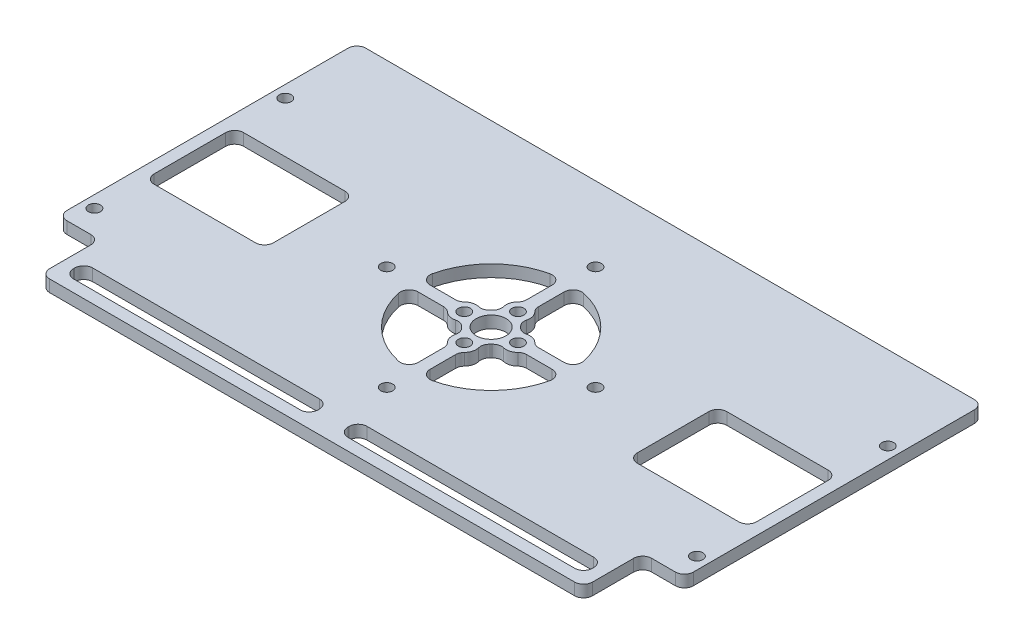
SolidWorks part; units mm, degrees
ref_plane "Front Plane" through (0, 0, 0) normal (0, 0, 1) x (1, 0, 0)
ref_plane "Top Plane" through (0, 0, 0) normal (0, 1, 0) x (1, 0, 0)
ref_plane "Right Plane" through (0, 0, 0) normal (1, 0, 0) x (0, 0, -1)
sketch "Sketch2" plane through (0, 0, 0) normal (0, 1, 0) x (1, 0, 0)
  line L0 (0, -30) -> (105, -30) construction
  line L1 (0, 0) -> (105, 0)
  line L2 (0, 0) -> (0, -60)
  line L3 (0, -60) -> (105, -60)
  line L4 (105, 0) -> (105, -60)
  line L5 (52.5, 0) -> (52.5, -60) construction
  line L6 (55, -54.8) -> (55, -58)
  line L7 (9, -54.8) -> (50, -54.8)
  line L8 (9, -54.8) -> (9, -58)
  line L9 (9, -58) -> (50, -58)
  line L10 (50, -54.8) -> (50, -58)
  line L11 (96, -54.8) -> (96, -58)
  line L12 (96, -58) -> (55, -58)
  line L13 (96, -54.8) -> (55, -54.8)
  line L14 (51.5, -17.0385) -> (51.5, -23.7679)
  line L15 (53.5, -17.0385) -> (53.5, -23.7679)
  line L16 (65.4615, -29) -> (58.7321, -29)
  line L17 (65.4615, -31) -> (58.7321, -31)
  line L18 (53.5, -42.9615) -> (53.5, -36.2321)
  line L19 (51.5, -42.9615) -> (51.5, -36.2321)
  line L20 (39.5385, -31) -> (46.2679, -31)
  line L21 (39.5385, -29) -> (46.2679, -29)
  line L22 (0, -50.1) -> (7, -50.1)
  line L23 (7, -50.1) -> (7, -60)
  line L24 (98, -50.1) -> (98, -60)
  line L25 (105, -50.1) -> (98, -50.1)
  line L26 (83, -22.5) -> (83, -37.5)
  line L27 (2, -22.5) -> (22, -22.5)
  line L28 (2, -22.5) -> (2, -37.5)
  line L29 (2, -37.5) -> (22, -37.5)
  line L30 (22, -22.5) -> (22, -37.5)
  line L31 (2, -22.5) -> (22, -37.5) construction
  line L32 (2, -37.5) -> (22, -22.5) construction
  line L33 (103, -22.5) -> (103, -37.5)
  line L34 (103, -37.5) -> (83, -37.5)
  line L35 (103, -22.5) -> (83, -22.5)
  circle A0 centre (2, -14) radius 1
  circle A1 centre (2, -46) radius 1
  circle A2 centre (103, -46) radius 1
  circle A3 centre (103, -14) radius 1
  arc A4 (51.5, -17.0385) -> (39.5385, -29) centre (52.5, -30) ccw
  circle A5 centre (52.5, -30) radius 2.5
  circle A6 centre (52.5, -25.5) radius 1
  circle A7 centre (52.5, -34.5) radius 1
  circle A8 centre (48, -30) radius 1
  circle A9 centre (57, -30) radius 1
  arc A10 (53.9907, -26.8333) -> (53.5, -23.7679) centre (52.5, -25.5) ccw
  arc A11 (51.0093, -26.8333) -> (49.3333, -28.5093) centre (52.5, -30) ccw
  circle A12 centre (52.5, -25.5) radius 2 construction
  circle A13 centre (52.5, -30) radius 3.5 construction
  arc A14 (55.6667, -31.4907) -> (58.7321, -31) centre (57, -30) ccw
  arc A15 (51.0093, -33.1667) -> (51.5, -36.2321) centre (52.5, -34.5) ccw
  arc A16 (49.3333, -28.5093) -> (46.2679, -29) centre (48, -30) ccw
  arc A17 (49.3333, -31.4907) -> (51.0093, -33.1667) centre (52.5, -30) ccw
  arc A18 (53.9907, -33.1667) -> (55.6667, -31.4907) centre (52.5, -30) ccw
  arc A19 (55.6667, -28.5093) -> (53.9907, -26.8333) centre (52.5, -30) ccw
  arc A20 (51.5, -23.7679) -> (51.0093, -26.8333) centre (52.5, -25.5) ccw
  arc A21 (46.2679, -31) -> (49.3333, -31.4907) centre (48, -30) ccw
  arc A22 (39.5385, -31) -> (51.5, -42.9615) centre (52.5, -30) ccw
  arc A23 (58.7321, -29) -> (55.6667, -28.5093) centre (57, -30) ccw
  arc A24 (65.4615, -29) -> (53.5, -17.0385) centre (52.5, -30) ccw
  arc A25 (53.5, -36.2321) -> (53.9907, -33.1667) centre (52.5, -34.5) ccw
  arc A26 (53.5, -42.9615) -> (65.4615, -31) centre (52.5, -30) ccw
  circle A27 centre (52.5, -30) radius 15 construction
  circle A28 centre (52.5, -30) radius 17.5 construction
  circle A29 centre (52.5, -12.5) radius 1
  circle A30 centre (70, -30) radius 1
  circle A31 centre (52.5, -47.5) radius 1
  circle A32 centre (35, -30) radius 1
  point P54 (52.5, -30)
  point P71 (52.5, -30)
  point P81 (52.5, -30)
  point P85 (12, -30)
  dimension "D3" = 2
  dimension "D4" = 2
  dimension "D5" = 16
  dimension "D10" = 26
  dimension "D11" = 5
  dimension "D12" = 2
  dimension "D13" = 4.5
  dimension "D14" = 4.5
  dimension "D20" = 30
  dimension "D21" = 35
  dimension "D22" = 4
  dimension "D1" = 105
  dimension "D2" = 60
  dimension "D6" = 3.2
  dimension "D7" = 2.5
  dimension "D8" = 4.1
  dimension "D9" = 2
  dimension "D18" = 1
  dimension "D23" = 7
  dimension "D24" = 2
  dimension "D25" = 20
  dimension "D26" = 15
  dimension "D27" = 2
  dimension "D15" = 1
  dimension "D16" = 1
  dimension "D17" = 4
  dimension "D19" = 4
extrude "Boss-Extrude1" add sketch "Sketch2" along normal blind 2 contours L25 L4 L1 L2 L22 L23 L3 L24 A32 A31 A30 A29 A26 L18 A25 A18 A14 L17 A24 L16 A23 A19 A10 L15 A22 L20 A21 A17 A15 L19 A7 A6 A5 A1 A0 L13 L11 L12
fillet "Fillet1" radius 1.5 48 edges at (39.5385, 1, 29) (46.2679, 1, 29) (49.3333, 1, 28.5093) (51.0093, 1, 26.8333) (51.5, 1, 23.7679) (2, 1, 22.5) (2, 1, 37.5) (22, 1, 37.5) (22, 1, 22.5) (9, 1, 54.8) (9, 1, 58) (50, 1, 58) (50, 1, 54.8) (55, 1, 54.8) (55, 1, 58) (96, 1, 58) (96, 1, 54.8) (98, 1, 50.1) (98, 1, 60) (7, 1, 60) (7, 1, 50.1) (0, 1, 50.1) (0, 1, 0) (105, 1, 0) (105, 1, 50.1) (83, 1, 22.5) (83, 1, 37.5) (103, 1, 37.5) (103, 1, 22.5) (51.5, 1, 42.9615) (51.5, 1, 36.2321) (51.0093, 1, 33.1667) (49.3333, 1, 31.4907) (46.2679, 1, 31) (39.5385, 1, 31) (53.5, 1, 17.0385) (53.5, 1, 23.7679) (53.9907, 1, 26.8333) (55.6667, 1, 28.5093) (58.7321, 1, 29) (65.4615, 1, 29) (65.4615, 1, 31) (58.7321, 1, 31) (55.6667, 1, 31.4907) (53.9907, 1, 33.1667) (53.5, 1, 36.2321) (53.5, 1, 42.9615) (51.5, 1, 17.0385)
